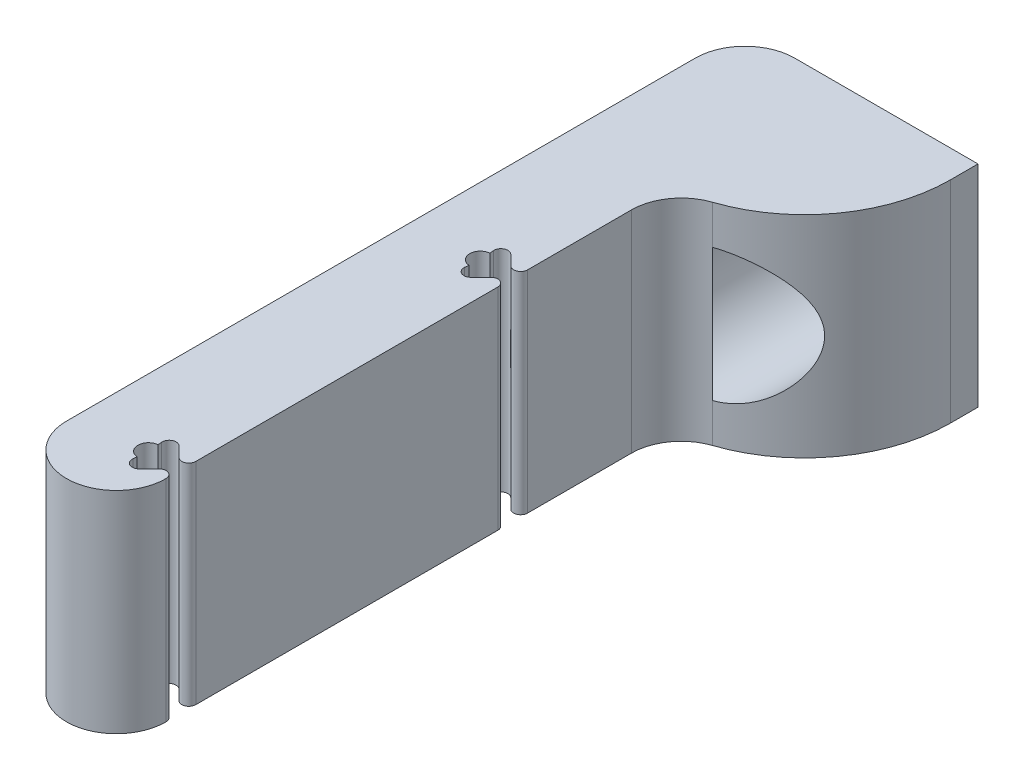
SolidWorks part; units mm, degrees
material "6061 Alloy"
ref_plane "Front Plane" through (0, 0, 0) normal (0, 0, 1) x (1, 0, 0)
ref_plane "Top Plane" through (0, 0, 0) normal (0, 1, 0) x (1, 0, 0)
ref_plane "Right Plane" through (0, 0, 0) normal (1, 0, 0) x (0, 0, -1)
sketch "Sketch1" plane through (0, 0, 0) normal (0, 1, 0) x (1, 0, 0)
  line L0 (0, 0) -> (-4, 0) construction
  line L1 (-4, 0) -> (-4.0553, 0.6326) construction
  line L2 (-4.0553, 0.6326) -> (-4.0758, 0.8669)
  line L3 (-3.3615, 1.2) -> (-2.7615, 0.6)
  line L4 (-4, 0) -> (-3.0808, 0.9192) construction
  line L5 (-6.465, 0.8965) -> (-2.465, 0.8965) construction
  line L6 (-4.0553, -0.6326) -> (-4.0758, -0.8669)
  line L7 (-3.3615, -1.2) -> (-2.7615, -0.6)
  line L47 (-4.0553, 20.6326) -> (-4.0758, 20.8669)
  line L48 (-3.3615, 21.2) -> (-2.7615, 20.6)
  line L49 (-4.0553, 19.3674) -> (-4.0758, 19.1331)
  line L50 (-3.3615, 18.8) -> (-2.7615, 19.4)
  line L51 (-2.0456, 20.8965) -> (-2.0456, 27.1559)
  line L53 (-4, 20) -> (-4.0553, 20.6326) construction
  line L54 (-4, 20) -> (-3.0808, 20.9192) construction
  line L55 (-4.0553, 0.6326) -> (-4.0553, 20.6326) construction
  line L57 (-2.0456, 19.1035) -> (-2.0456, 0.8965)
  line L58 (-8.0456, -0.8965) -> (-8.0456, 37)
  line L60 (0, 0) -> (0, 14.063) construction
  line L64 (6, 38.3422) -> (6, 40)
  line L65 (6, 40) -> (-5.0456, 40)
  line L67 (-5.0456, -0.8965) -> (-2.465, -0.8965) construction
  circle A0 centre (-4, 0) radius 0.635 construction
  arc A1 (-4.0758, 0.8669) -> (-3.3615, 1.2) centre (-3.6581, 0.9035) cw
  arc A2 (-2.7615, 0.6) -> (-2.0456, 0.8965) centre (-2.465, 0.8965) ccw
  arc A4 (-4.0553, 0.6326) -> (-4.0553, -0.6326) centre (-4, 0) ccw
  arc A5 (-4.0758, -0.8669) -> (-3.3615, -1.2) centre (-3.6581, -0.9035) ccw
  arc A6 (-2.7615, -0.6) -> (-2.0456, -0.8965) centre (-2.465, -0.8965) cw
  arc A87 (-4.0758, 20.8669) -> (-3.3615, 21.2) centre (-3.6581, 20.9035) cw
  arc A88 (-2.7615, 20.6) -> (-2.0456, 20.8965) centre (-2.465, 20.8965) ccw
  arc A89 (-4.0553, 20.6326) -> (-4.0553, 19.3674) centre (-4, 20) ccw
  arc A90 (-4.0758, 19.1331) -> (-3.3615, 18.8) centre (-3.6581, 19.0965) ccw
  arc A91 (-2.7615, 19.4) -> (-2.0456, 19.1035) centre (-2.465, 19.1035) cw
  circle A92 centre (-4, 20) radius 0.635 construction
  arc A93 (-2.0456, -0.8965) -> (-8.0456, -0.8965) centre (-5.0456, -0.8965) cw
  arc A94 (-2.0456, 27.1559) -> (0, 30) centre (0.9544, 27.1559) cw
  arc A95 (0, 30) -> (6, 38.3422) centre (-2.7994, 38.3422) ccw
  arc A96 (-8.0456, 37) -> (-5.0456, 40) centre (-5.0456, 37) cw
  point P0 (0, 0)
  dimension "D1" = 1.27
  dimension "D13" = 10
  dimension "D8" = 2
  dimension "D10" = 10
  dimension "D11" = 3
  dimension "D9" = 20
  dimension "D12" = 6
  dimension "D2" = 4
  dimension "D3" = 95
  dimension "D4" = 45
  dimension "D5" = 1.2
  dimension "D6" = 1.3
  dimension "D7" = 0.6
extrude "Boss-Extrude1" add sketch "Sketch1" along normal blind 12.7
sketch "Sketch2" plane through (0, 0, -40) normal (0, 0, -1) x (-1, 0, 0)
  line L0 (-6, 12.7) -> (-6, 0) construction
  line L1 (-6, 6.35) -> (0, 6.35) construction
  circle A0 centre (0, 6.35) radius 4
  dimension "D1" = 6
  dimension "D2" = 8
extrude "Cut-Extrude1" cut sketch "Sketch2" against normal blind 10
